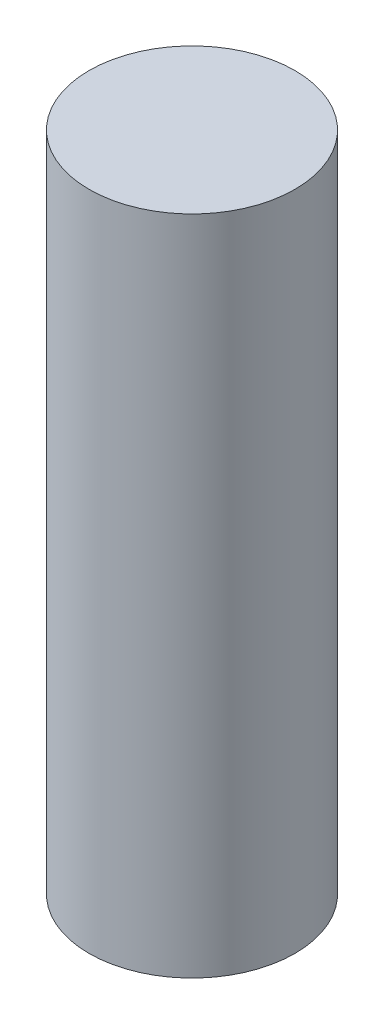
SolidWorks part; units mm, degrees
ref_plane "前视基准面" through (0, 0, 0) normal (0, 0, 1) x (1, 0, 0)
ref_plane "上视基准面" through (0, 0, 0) normal (0, 1, 0) x (1, 0, 0)
ref_plane "右视基准面" through (0, 0, 0) normal (1, 0, 0) x (0, 0, -1)
other "Configuration Table"
sketch "草图1" plane through (0, 0, 0) normal (0, 1, 0) x (1, 0, 0)
  circle A0 centre (0, 0) radius 7
  dimension "D1" = 14
extrude "凸台-拉伸1" add sketch "草图1" along normal blind 45
